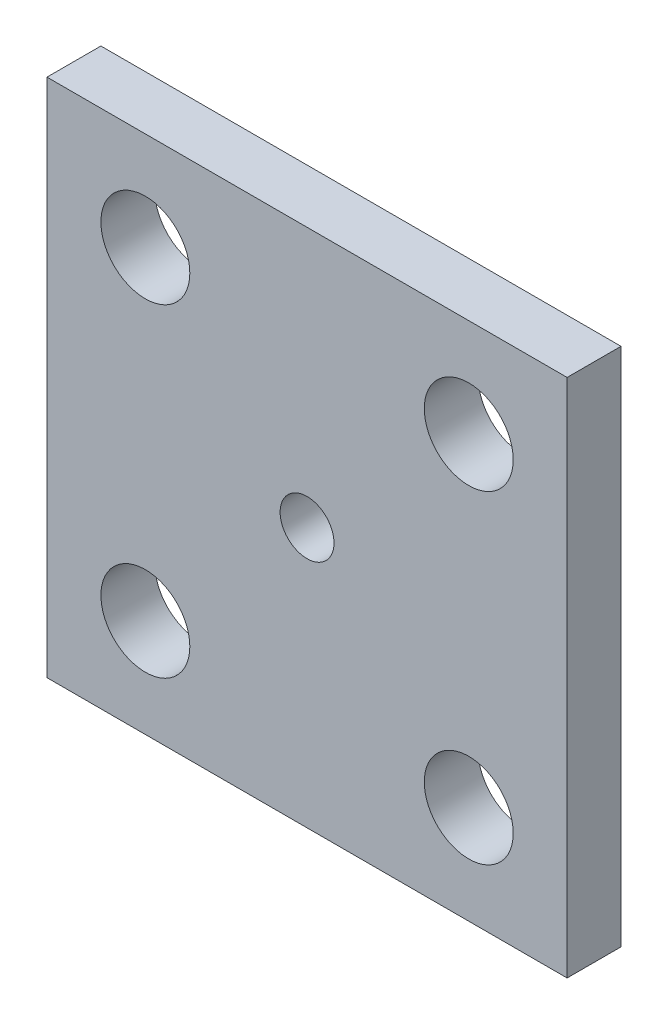
SolidWorks part; units mm, degrees
material "Acrylic (Medium-high impact)"
ref_plane "Front Plane" through (0, 0, 0) normal (0, 0, 1) x (1, 0, 0)
ref_plane "Top Plane" through (0, 0, 0) normal (0, 1, 0) x (1, 0, 0)
ref_plane "Right Plane" through (0, 0, 0) normal (1, 0, 0) x (0, 0, -1)
sketch "Sketch1" plane through (0, 0, 0) normal (0, 0, 1) x (1, 0, 0)
  line L0 (39.125, 39.125) -> (9.125, 9.125) construction
  line L1 (0, 0) -> (48.25, 0)
  line L2 (0, 0) -> (0, 48.25)
  line L3 (0, 48.25) -> (48.25, 48.25)
  line L4 (48.25, 0) -> (48.25, 48.25)
  line L5 (9.125, 9.125) -> (39.125, 9.125) construction
  line L6 (9.125, 9.125) -> (9.125, 39.125) construction
  line L7 (9.125, 39.125) -> (39.125, 39.125) construction
  line L8 (39.125, 9.125) -> (39.125, 39.125) construction
  line L9 (5, 9.125) -> (0, 9.125) construction
  line L10 (34.8959, 1.8) -> (30.6668, 9.125)
  line L11 (17.5832, 9.125) -> (13.3541, 16.45)
  line L12 (13.3541, 16.45) -> (4.8959, 16.45)
  line L13 (4.8959, 16.45) -> (0.6668, 9.125)
  line L14 (0.6668, 9.125) -> (4.8959, 1.8)
  line L15 (4.8959, 1.8) -> (13.3541, 1.8)
  line L16 (13.3541, 1.8) -> (17.5832, 9.125)
  line L17 (43.3541, 1.8) -> (34.8959, 1.8)
  line L18 (47.5832, 9.125) -> (43.3541, 1.8)
  line L19 (43.3541, 16.45) -> (47.5832, 9.125)
  line L20 (9.125, 24.125) -> (0, 24.125) construction
  line L21 (24.125, 9.125) -> (24.125, 0) construction
  line L22 (34.8959, 16.45) -> (43.3541, 16.45)
  line L23 (30.6668, 9.125) -> (34.8959, 16.45)
  line L24 (43.3541, 31.8) -> (47.5832, 39.125)
  line L25 (47.5832, 39.125) -> (43.3541, 46.45)
  line L26 (43.3541, 46.45) -> (34.8959, 46.45)
  line L27 (34.8959, 46.45) -> (30.6668, 39.125)
  line L28 (30.6668, 39.125) -> (34.8959, 31.8)
  line L29 (34.8959, 31.8) -> (43.3541, 31.8)
  line L30 (4.8959, 31.8) -> (0.6668, 39.125)
  line L31 (0.6668, 39.125) -> (4.8959, 46.45)
  line L32 (4.8959, 46.45) -> (13.3541, 46.45)
  line L33 (13.3541, 46.45) -> (17.5832, 39.125)
  line L34 (17.5832, 39.125) -> (13.3541, 31.8)
  line L35 (13.3541, 31.8) -> (4.8959, 31.8)
  circle A0 centre (9.125, 9.125) radius 4.125
  circle A1 centre (9.125, 9.125) radius 7.325 construction
  circle A2 centre (39.125, 9.125) radius 4.125
  circle A3 centre (39.125, 39.125) radius 4.125
  circle A4 centre (24.125, 24.125) radius 2.5
  circle A5 centre (9.125, 39.125) radius 4.125
  text T0 "                 LD 5mm\r\n                 5mW" font "Century Gothic" height 1.5
  point P47 (24.125, 39.125)
  dimension "D2" = 8.25
  dimension "D3" = 5
  dimension "D4" = 5
  dimension "D1" = 30
  dimension "D5" = 14.65
extrude "Boss-Extrude1" add sketch "Sketch1" along normal blind 5 contours L35 L34 L33 L32 L31 L30 A5 | L15 L16 L11 L12 L13 L14 A0 | L23 L10 L17 L18 L19 L22 A2 | L28 L29 L24 L25 L26 L27 A3 | L1 L4 L3 L2 A4 L10 L23 L22 L19 L18 L17 L16 L15 L14 L13 L12 L11 L29 L28 L27 L26 L25 L24 L34 L35 L30 L31 L32 L33
